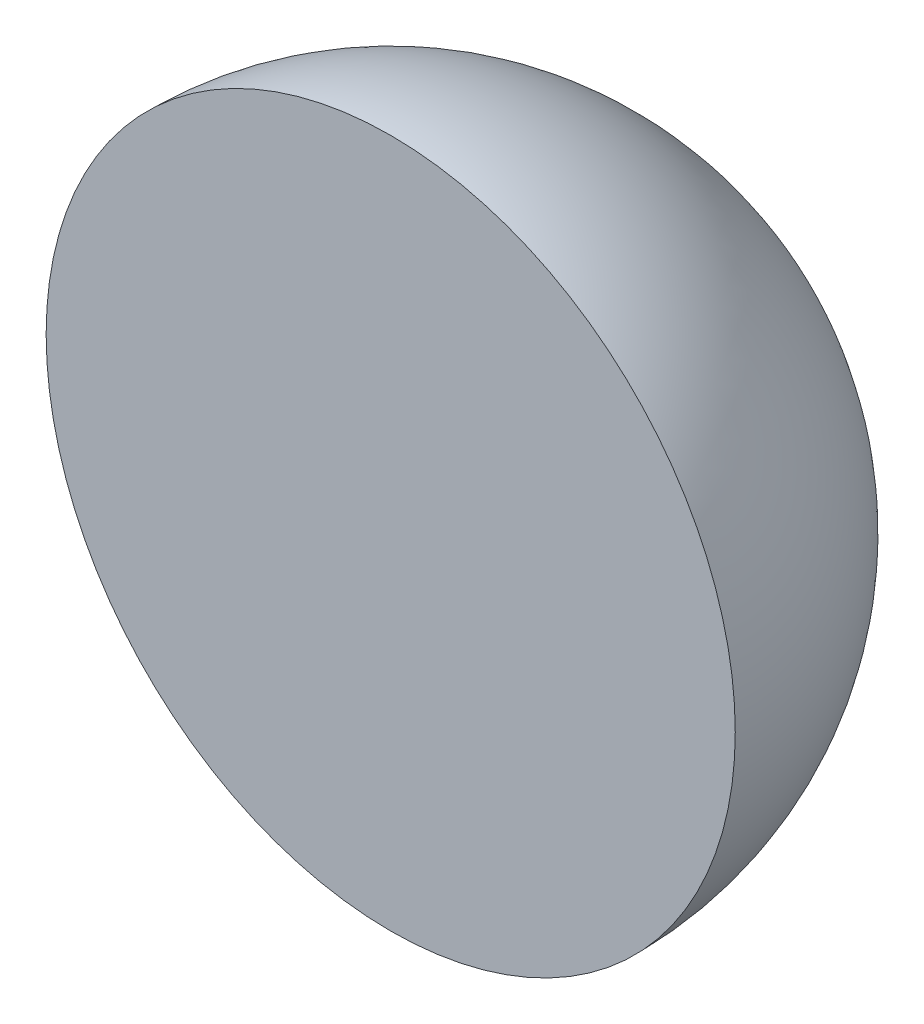
SolidWorks part; units mm, degrees
ref_plane "Front Plane" through (0, 0, 0) normal (0, 0, 1) x (1, 0, 0)
ref_plane "Top Plane" through (0, 0, 0) normal (0, 1, 0) x (1, 0, 0)
ref_plane "Right Plane" through (0, 0, 0) normal (1, 0, 0) x (0, 0, -1)
sketch "Sketch1" plane through (0, 0, 0) normal (0, 1, 0) x (1, 0, 0)
  line L0 (0, 42) -> (0, 0)
  line L1 (0, 0) -> (42, 0)
  arc A0 (42, 0) -> (0, 42) centre (0, 0) ccw
  dimension "D1" = 42
revolve "Revolve1" add sketch "Sketch1" angle 360 about L0
